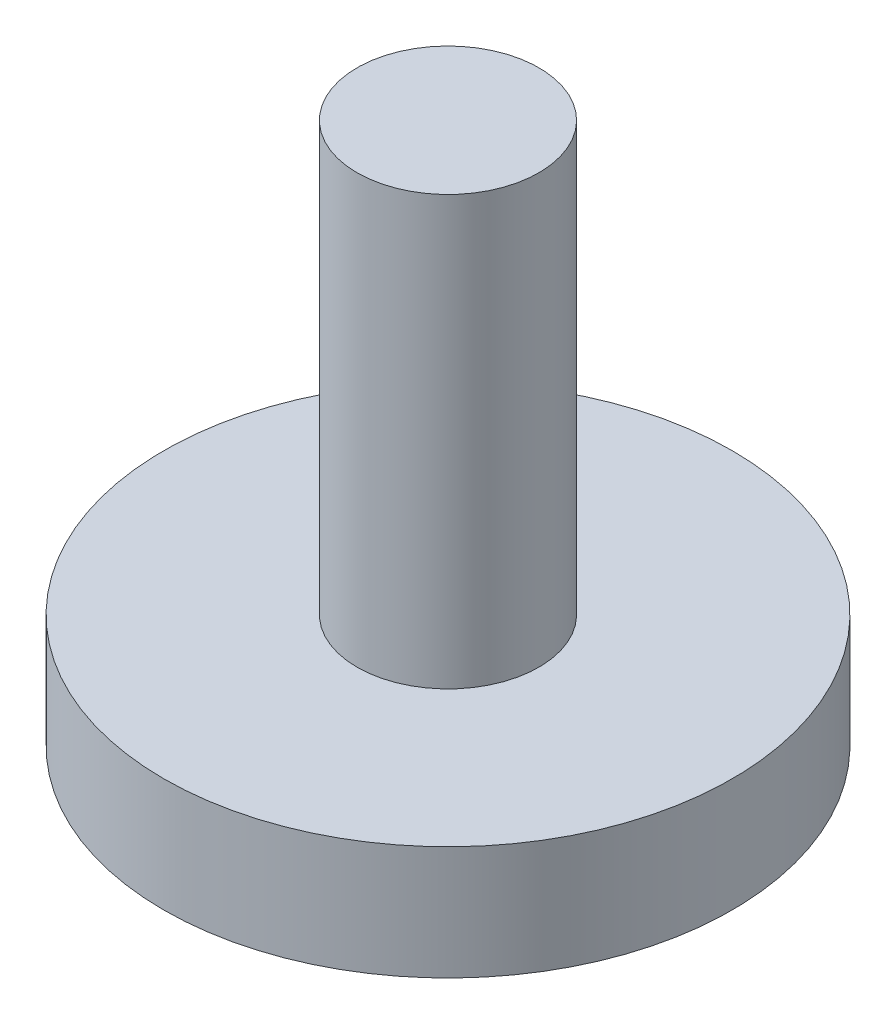
SolidWorks part; units mm, degrees
ref_plane "Front Plane" through (0, 0, 0) normal (0, 0, 1) x (1, 0, 0)
ref_plane "Top Plane" through (0, 0, 0) normal (0, 1, 0) x (1, 0, 0)
ref_plane "Right Plane" through (0, 0, 0) normal (1, 0, 0) x (0, 0, -1)
sketch "Sketch1" plane through (0, 0, 0) normal (0, 1, 0) x (1, 0, 0)
  circle A0 centre (0, 0) radius 7.5
  dimension "D1" = 15
extrude "Boss-Extrude1" add sketch "Sketch1" along normal blind 3
sketch "Sketch2" plane through (0, 3, 0) normal (0, 1, 0) x (1, 0, 0)
  circle A0 centre (0, 0) radius 2.4
  dimension "D1" = 4.8
extrude "Boss-Extrude2" add sketch "Sketch2" along normal blind 11.3
